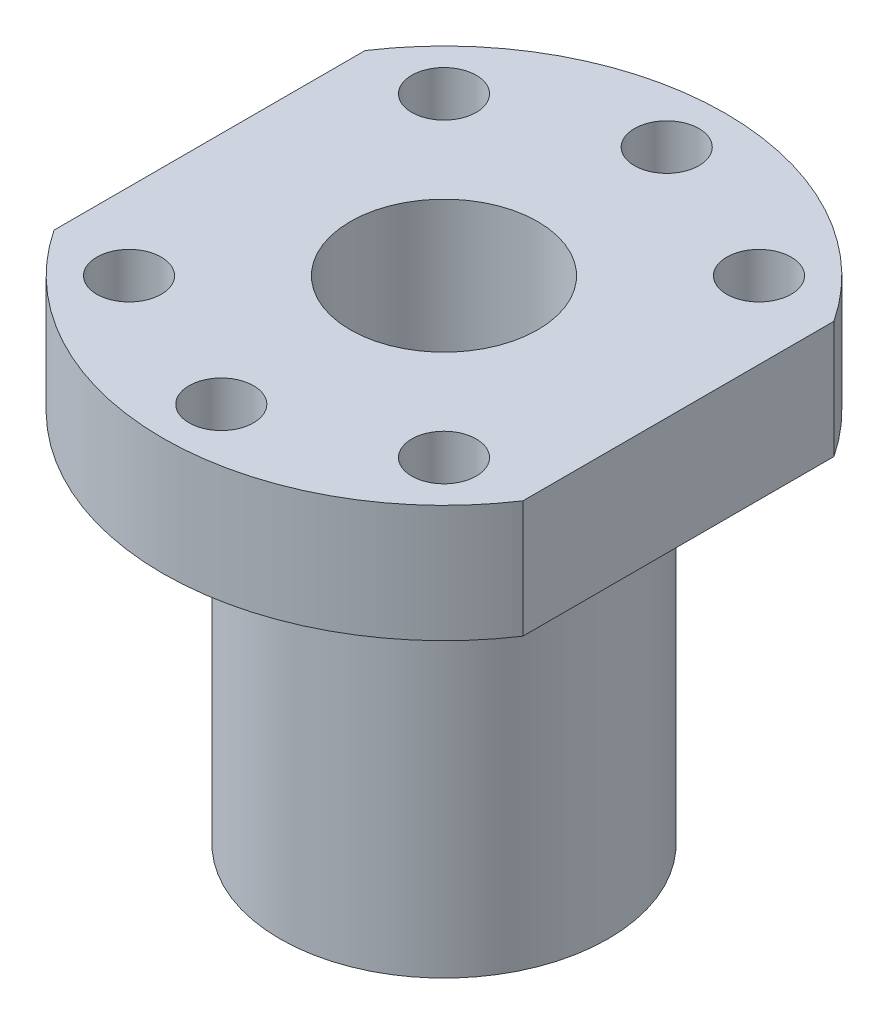
SolidWorks part; units mm, degrees
ref_plane "Front Plane" through (0, 0, 0) normal (0, 0, 1) x (1, 0, 0)
ref_plane "Top Plane" through (0, 0, 0) normal (0, 1, 0) x (1, 0, 0)
ref_plane "Right Plane" through (0, 0, 0) normal (1, 0, 0) x (0, 0, -1)
sketch "Sketch1" plane through (0, 0, 0) normal (0, 0, 1) x (1, 0, 0)
  line L0 (0, 0) -> (0, 84) construction
  line L1 (0, 0) -> (14, 0)
  line L2 (14, 0) -> (14, 32)
  line L3 (14, 32) -> (24, 32)
  line L4 (24, 32) -> (24, 42)
  line L5 (24, 42) -> (0, 42)
  line L6 (0, 42) -> (0, 0)
  dimension "D1" = 42
  dimension "D2" = 10
  dimension "D3" = 48
  dimension "D4" = 28
revolve "Revolve1" add sketch "Sketch1" angle 360 about L0
sketch "Sketch2" plane through (0, 42, 0) normal (0, 1, 0) x (1, 0, 0)
  line L0 (0, 0) -> (0, 42.7665) construction
  line L1 (-20, 13.2665) -> (-20, -13.2665)
  line L2 (20, 13.2665) -> (20, -13.2665)
  circle A0 centre (0, 0) radius 24 construction
  arc A1 (-20, 13.2665) -> (-20, -13.2665) centre (0, 0) ccw
  arc A2 (20, -13.2665) -> (20, 13.2665) centre (0, 0) ccw
  dimension "D1" = 40
extrude "Cut-Extrude1" cut sketch "Sketch2" against normal through all both
sketch "Sketch3" plane through (0, 42, 0) normal (0, 1, 0) x (1, 0, 0)
  line L0 (0, 0) -> (0, 19) construction
  line L1 (0, 0) -> (0, -19) construction
  line L2 (-13.435, -13.435) -> (13.435, 13.435) construction
  line L3 (13.435, -13.435) -> (-13.435, 13.435) construction
  circle A0 centre (0, 0) radius 19 construction
  circle A1 centre (0, 19) radius 2.75
  circle A2 centre (0, -19) radius 2.75
  circle A3 centre (-13.435, 13.435) radius 2.75
  circle A4 centre (13.435, 13.435) radius 2.75
  circle A5 centre (13.435, -13.435) radius 2.75
  circle A6 centre (-13.435, -13.435) radius 2.75
  point P10 (0, 0)
  point P13 (0, 0)
  dimension "D1" = 38
  dimension "D4" = 5.5
  dimension "D2" = 45
  dimension "D3" = 45
extrude "Cut-Extrude2" cut sketch "Sketch3" against normal through all both
sketch "Sketch4" plane through (0, 42, 0) normal (0, 1, 0) x (1, 0, 0)
  circle A0 centre (0, 0) radius 8
  dimension "D1" = 16
extrude "Cut-Extrude3" cut sketch "Sketch4" against normal through all
